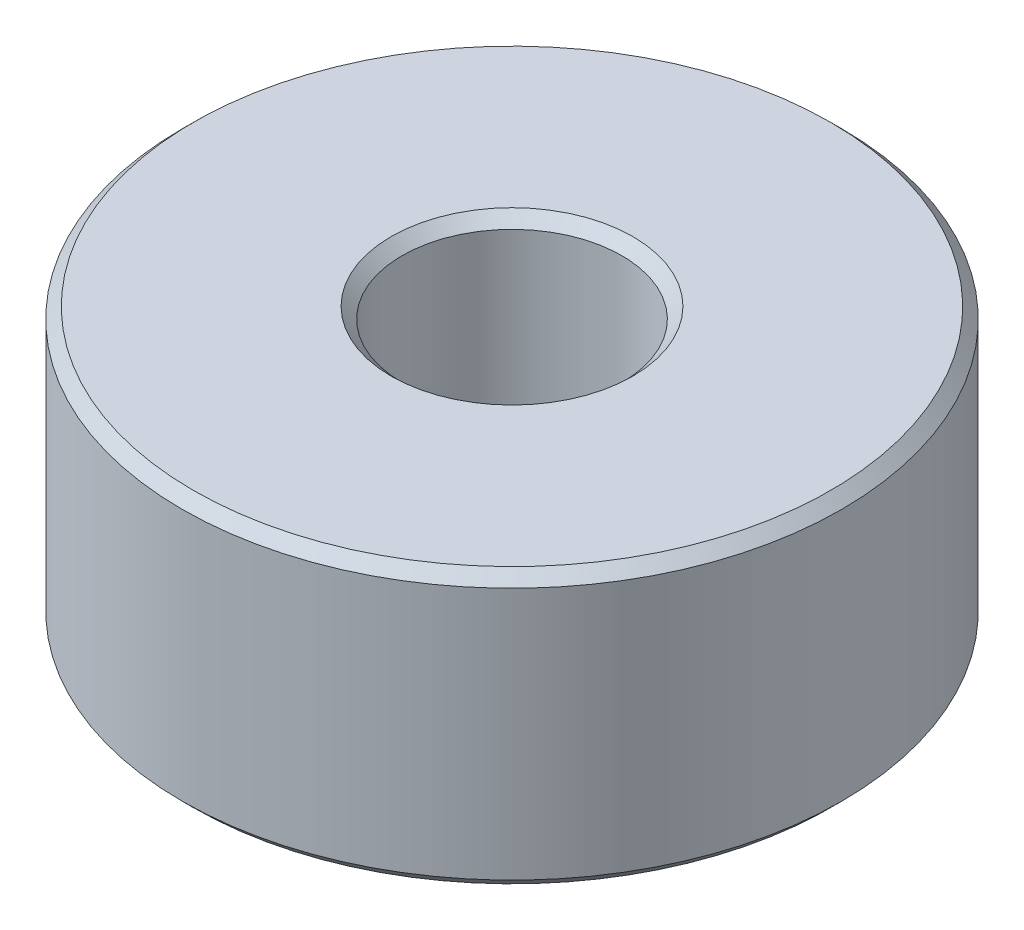
SolidWorks part; units mm, degrees
ref_plane "Front Plane" through (0, 0, 0) normal (0, 0, 1) x (1, 0, 0)
ref_plane "Top Plane" through (0, 0, 0) normal (0, 1, 0) x (1, 0, 0)
ref_plane "Right Plane" through (0, 0, 0) normal (1, 0, 0) x (0, 0, -1)
sketch "Sketch1" plane through (0, 0, 0) normal (0, 1, 0) x (1, 0, 0)
  circle A0 centre (0, 0) radius 3
  circle A1 centre (0, 0) radius 1
  dimension "D1" = 6
  dimension "D2" = 2
extrude "Boss-Extrude1" add sketch "Sketch1" along normal blind 2.5
chamfer "Chamfer1" distance 0.1 angle 45 4 edges at (0, 0, 1) (0, 0, 3) (0, 2.5, 1) (0, 2.5, 3)
